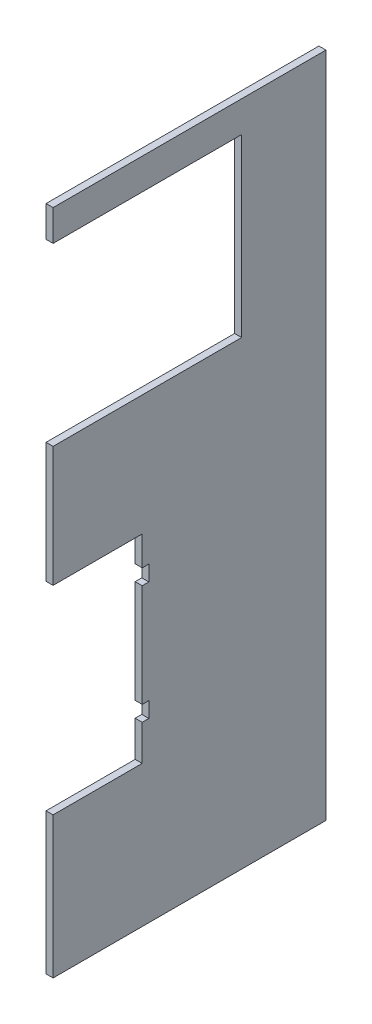
SolidWorks part; units mm, degrees
ref_plane "Спереди" through (0, 0, 0) normal (0, 0, 1) x (1, 0, 0)
ref_plane "Сверху" through (0, 0, 0) normal (0, 1, 0) x (1, 0, 0)
ref_plane "Справа" through (0, 0, 0) normal (1, 0, 0) x (0, 0, -1)
ref_plane "Плоскость4" through (0.5, 0, 0) normal (-1, 0, 0) x (0, -1, 0)
sketch "Эскиз1" plane through (0.5, 0, 0) normal (-1, 0, 0) x (0, -1, 0)
  line L0 (-5.85, 42.25) -> (-100.85, 42.25)
  line L1 (-100.85, 42.25) -> (-100.85, 3.4)
  line L2 (-100.85, 3.4) -> (-5.85, 3.4)
  line L3 (-5.85, 3.4) -> (-5.85, 42.25)
extrude "Бобышка-Вытянуть1" add sketch "Эскиз1" against normal blind 0.5
sketch "Эскиз2" plane through (0.5, 0, 0) normal (-1, 0, 0) x (0, 0, 1)
  line L0 (42.25, 5.85) -> (3.4, 5.85)
  line L1 (3.4, 5.85) -> (3.4, 100.85)
  line L2 (3.4, 100.85) -> (42.25, 100.85)
  line L3 (42.25, 100.85) -> (42.25, 5.85)
extrude "Бобышка-Вытянуть2" add sketch "Эскиз2" along normal blind 0.5
sketch "Эскиз3" plane through (0, 0, 0) normal (-1, 0, 0) x (0, 0, 1)
  line L1 (47.1872, 54.262) -> (29.5623, 54.262)
  line L2 (47.1872, 54.262) -> (47.1872, 25.9692)
  line L3 (47.1872, 25.9692) -> (29.5623, 25.9692)
  line L4 (29.5623, 54.262) -> (29.5623, 25.9692) construction
  line L5 (29.5623, 54.262) -> (29.5623, 50.0787)
  line L6 (44.6087, 96.4292) -> (15.4063, 96.4292)
  line L7 (44.6087, 96.4292) -> (44.6087, 71.4049)
  line L8 (44.6087, 71.4049) -> (15.4063, 71.4049)
  line L9 (15.4063, 96.4292) -> (15.4063, 71.4049)
  line L10 (29.5623, 50.0787) -> (28.6189, 50.0787)
  line L11 (28.6189, 50.0787) -> (28.6189, 47.8787)
  line L12 (28.6189, 47.8787) -> (29.5623, 47.8787)
  line L13 (29.5623, 47.8787) -> (29.5623, 33.2387)
  line L14 (29.5623, 33.2387) -> (28.6189, 33.2387)
  line L15 (28.6189, 33.2387) -> (28.6189, 31.0387)
  line L16 (28.6189, 31.0387) -> (29.5623, 31.0387)
  line L17 (29.5623, 31.0387) -> (29.5623, 25.9692)
  line L18 (28.9189, 49.7787) -> (31.0057, 49.7787) construction
  line L19 (28.9189, 48.1787) -> (28.9189, 49.7787) construction
  line L20 (31.0057, 48.1787) -> (28.9189, 48.1787) construction
  line L21 (28.9189, 32.9387) -> (31.0057, 32.9387) construction
  line L22 (28.9189, 31.3387) -> (28.9189, 32.9387) construction
  line L23 (31.0057, 31.3387) -> (28.9189, 31.3387) construction
  dimension "D1" = 0.3
  dimension "D2" = 0.3
  dimension "D3" = 0.3
  dimension "D4" = 0.3
  dimension "D5" = 0.3
  dimension "D6" = 0.3
extrude "Вырез-Вытянуть1" cut sketch "Эскиз3" against normal through all
